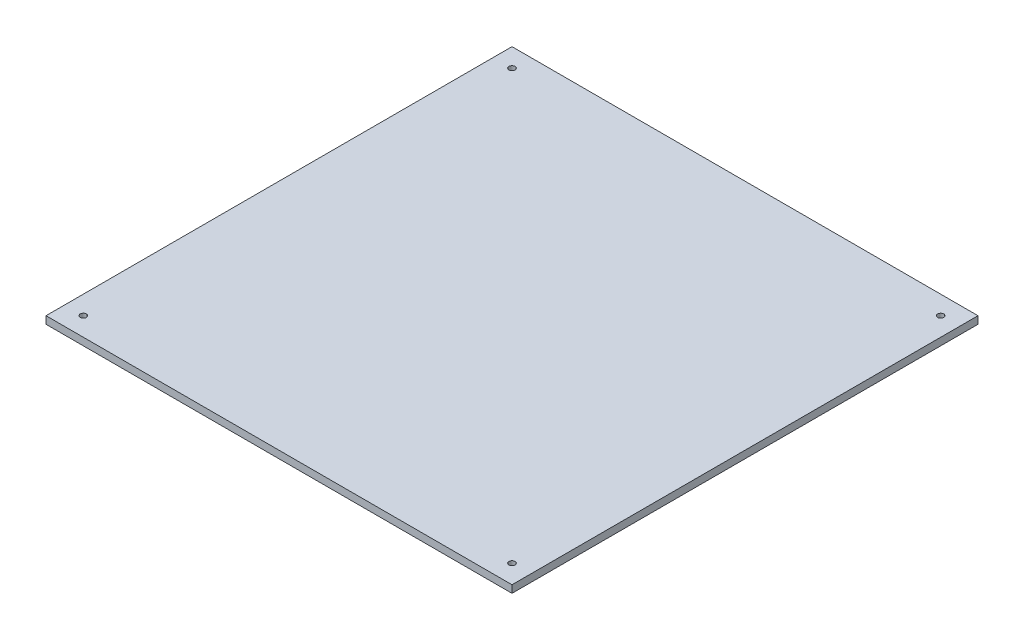
SolidWorks part; units mm, degrees
ref_plane "Front Plane" through (0, 0, 0) normal (0, 0, 1) x (1, 0, 0)
ref_plane "Top Plane" through (0, 0, 0) normal (0, 1, 0) x (1, 0, 0)
ref_plane "Right Plane" through (0, 0, 0) normal (1, 0, 0) x (0, 0, -1)
sketch "Sketch1" plane through (0, 0, 0) normal (0, 1, 0) x (1, 0, 0)
  line L0 (0, 125) -> (250, 125) construction
  line L1 (0, 0) -> (250, 0)
  line L2 (0, 0) -> (0, 250)
  line L3 (0, 250) -> (250, 250)
  line L4 (250, 0) -> (250, 250)
  line L5 (125, 250) -> (125, 0) construction
  circle A0 centre (10, 10) radius 1.65
  circle A1 centre (240, 10) radius 1.65
  circle A2 centre (240, 240) radius 1.65
  circle A3 centre (10, 240) radius 1.65
  dimension "D3" = 3.3
  dimension "D1" = 250
  dimension "D2" = 250
  dimension "D4" = 10
  dimension "D5" = 10
extrude "Boss-Extrude1" add sketch "Sketch1" along normal blind 4
equation "\"cf_tube_outer_diameter\" = 25mm"
equation "\"cf_tube_inner_diameter\" = 21mm"
equation "\"mid_plate_mid_to_top\" = 100mm"
equation "\"mid_plate_mid_to_bottom\" = 30mm"
equation "\"mid_plate_horizontal_spacing\" = 250mm"
equation "\"cf_plate_thickness\" = 4mm"
equation "\"mid_tube_length\" = 500mm"
equation "\"mid_plate_bottom_width\"= 150mm"
equation "\"D1@Sketch1\"=\"mid_plate_horizontal_spacing\""
equation "\"mid_support_plate_distance\" = 250mm"
equation "\"D2@Sketch1\"=\"mid_support_plate_distance\""
equation "\"D1@Boss-Extrude1\"=\"cf_plate_thickness\""
